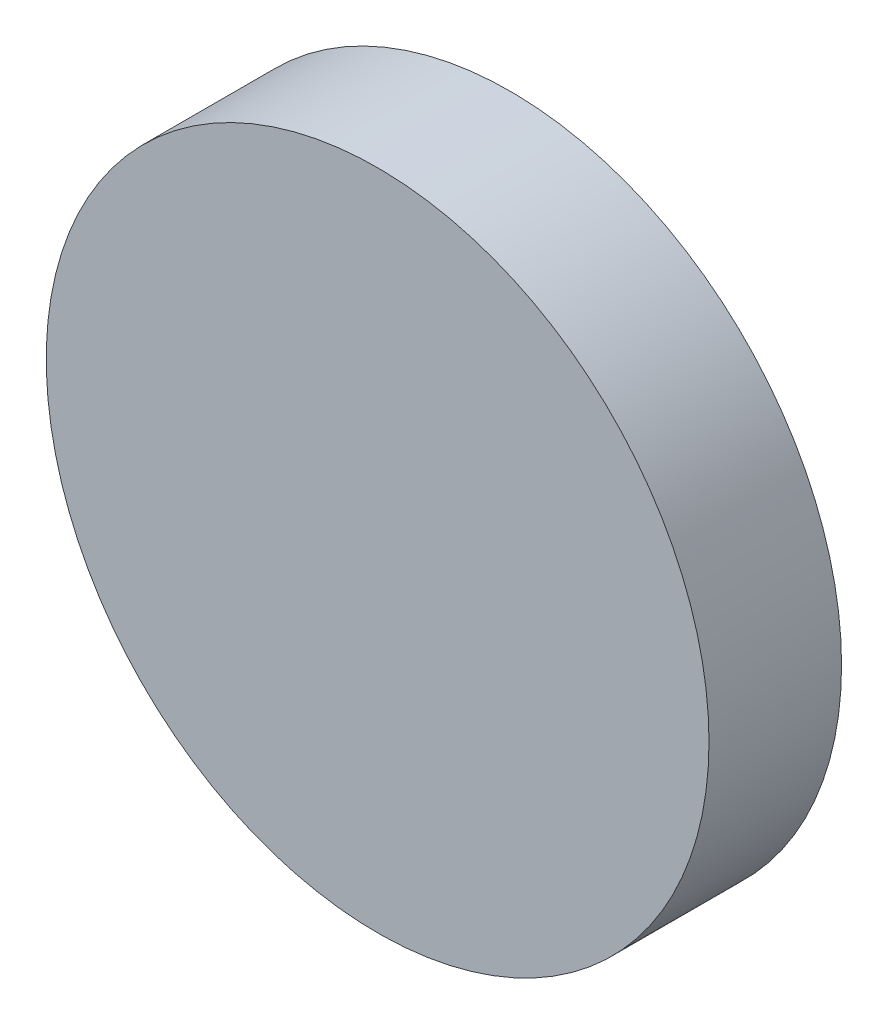
SolidWorks part; units mm, degrees
ref_plane "Front Plane" through (0, 0, 0) normal (0, 0, 1) x (1, 0, 0)
ref_plane "Top Plane" through (0, 0, 0) normal (0, 1, 0) x (1, 0, 0)
ref_plane "Right Plane" through (0, 0, 0) normal (1, 0, 0) x (0, 0, -1)
sketch "Sketch1" plane through (0, 0, 0) normal (0, 0, 1) x (1, 0, 0)
  circle A0 centre (2.5, 2.5) radius 2.5
  dimension "D1" = 5
extrude "Profile" add sketch "Sketch1" along normal blind 1
equation "\"Profile_Depth\" = 1mm"
equation "\"D1@Profile\" = \"Profile_Depth\""
equation "\"Profile_Sketch_1\" = 5mm"
equation "\"D1@Sketch1\" = \"Profile_Sketch_1\""
equation "\"EnvelopeWidth\" = 5mm"
equation "\"EnvelopeHeight\" = 5mm"
